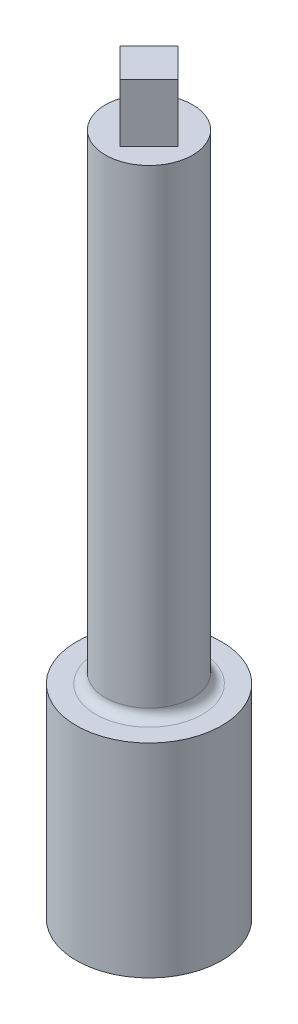
SolidWorks part; units mm, degrees
ref_plane "Front Plane" through (0, 0, 0) normal (0, 0, 1) x (1, 0, 0)
ref_plane "Top Plane" through (0, 0, 0) normal (0, 1, 0) x (1, 0, 0)
ref_plane "Right Plane" through (0, 0, 0) normal (1, 0, 0) x (0, 0, -1)
sketch "Sketch1" plane through (0, 0, 0) normal (0, 0, 1) x (1, 0, 0)
  line L0 (0, 0) -> (0, 24.9988) construction
  line L1 (0, 95.7119) -> (-9, 95.7119)
  line L2 (-9, 95.7119) -> (-9, -1.2881)
  line L3 (-11, -3.2881) -> (-15, -3.2881)
  line L4 (-15, -3.2881) -> (-15, -45.2881)
  line L5 (-15, -45.2881) -> (-6, -45.2881)
  line L6 (-6, -45.2881) -> (-6, -13.2881)
  line L7 (-6, -13.2881) -> (0, -13.2881)
  line L8 (0, -13.2881) -> (0, 95.7119)
  arc A0 (-9, -1.2881) -> (-11, -3.2881) centre (-11, -1.2881) cw
  dimension "D7" = 2
  dimension "D1" = 18
  dimension "D2" = 30
  dimension "D3" = 12
  dimension "D4" = 32
  dimension "D5" = 42
  dimension "D6" = 141
revolve "Revolve1" add sketch "Sketch1" angle 360 about L0
sketch "Sketch2" plane through (0, 95.7119, 0) normal (0, 1, 0) x (-1, 0, 0)
  line L1 (-6, 0) -> (0, -6)
  line L2 (0, -6) -> (6, 0)
  line L3 (6, 0) -> (0, 6)
  line L4 (0, 6) -> (-6, 0)
  circle A0 centre (0, 0) radius 4.2426 construction
  dimension "D1" = 12
extrude "Extrude1" add sketch "Sketch2" along normal blind 12
